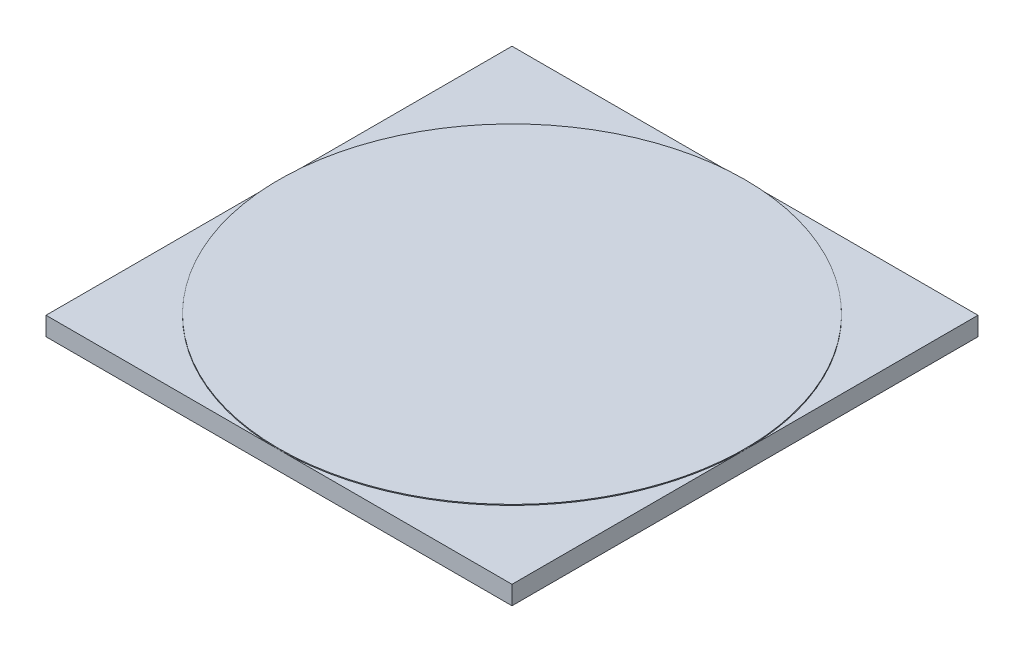
SolidWorks part; units mm, degrees
ref_plane "Front Plane" through (0, 0, 0) normal (0, 0, 1) x (1, 0, 0)
ref_plane "Top Plane" through (0, 0, 0) normal (0, 1, 0) x (1, 0, 0)
ref_plane "Right Plane" through (0, 0, 0) normal (1, 0, 0) x (0, 0, -1)
sketch "Sketch1" plane through (0, 0, 0) normal (0, 1, 0) x (1, 0, 0)
  line L1 (0, 0) -> (50, 0)
  line L2 (0, 0) -> (0, 50)
  line L3 (0, 50) -> (50, 50)
  line L4 (50, 0) -> (50, 50)
  line L5 (0, 0) -> (50, 50) construction
  line L6 (0, 50) -> (50, 0) construction
  point P4 (25, 25)
  dimension "D1" = 50
  dimension "D2" = 50
extrude "Boss-Extrude1" add sketch "Sketch1" along normal blind 2
sketch "Sketch2" plane through (0, 2, 0) normal (0, 1, 0) x (1, 0, 0)
  line L0 (0, 0) -> (50, 0) construction
  line L1 (0, 50) -> (0, 0) construction
  circle A0 centre (25, 25) radius 25
  dimension "D1" = 50
  dimension "D2" = 25
  dimension "D3" = 25
extrude "Boss-Extrude2" add sketch "Sketch2" along normal blind 0.1
